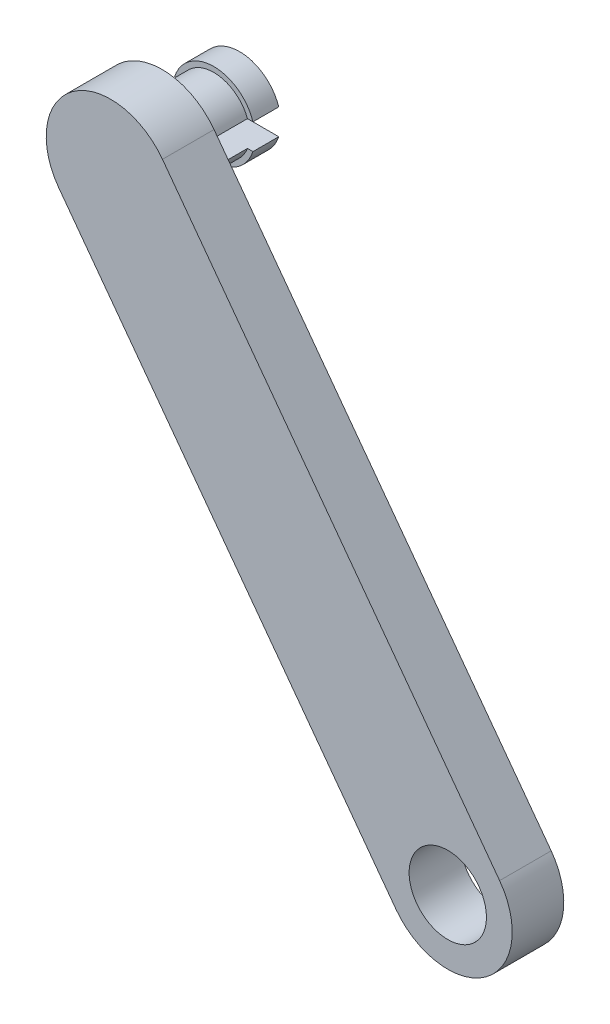
SolidWorks part; units mm, degrees
ref_plane "Plan de face" through (0, 0, 0) normal (0, 0, 1) x (1, 0, 0)
ref_plane "Plan de dessus" through (0, 0, 0) normal (0, 1, 0) x (1, 0, 0)
ref_plane "Plan de droite" through (0, 0, 0) normal (1, 0, 0) x (0, 0, -1)
sketch "Esquisse2" plane through (0, 0, 0) normal (0, 0, 1) x (1, 0, 0)
  line L0 (0, -5) -> (-13.0771, 12.6915) construction
  line L1 (-2.0104, -6.486) -> (-15.0875, 11.2054)
  line L2 (2.0104, -3.514) -> (-11.0667, 14.1775)
  arc A0 (-2.0104, -6.486) -> (2.0104, -3.514) centre (0, -5) ccw
  arc A1 (-11.0667, 14.1775) -> (-15.0875, 11.2054) centre (-13.0771, 12.6915) ccw
  point P4 (-6.5386, 3.8457)
  dimension "D1" = 5
extrude "Boss.-Extru.1" add sketch "Esquisse2" along normal blind 2
sketch "Esquisse3" plane through (0, 0, 2) normal (0, 0, 1) x (1, 0, 0)
  circle A0 centre (0, -5) radius 1.5
  dimension "D1" = 3
extrude "Enlèv. mat.-Extru.1" cut sketch "Esquisse3" against normal blind 2
sketch "Esquisse4" plane through (0, 0, 2) normal (0, 0, 1) x (1, 0, 0)
  circle A0 centre (-13.0771, 12.6915) radius 1.4
  dimension "D1" = 2.8
extrude "Boss.-Extru.2" add sketch "Esquisse4" against normal blind 2 from offset 2 offset against normal yes
sketch "Esquisse5" plane through (0, 0, -2) normal (0, 0, -1) x (-1, 0, 0)
  circle A0 centre (13.0771, 12.6915) radius 1.6
  dimension "D1" = 3.2
extrude "Boss.-Extru.3" add sketch "Esquisse5" along normal blind 1
sketch "Esquisse6" plane through (0, 0, -3) normal (0, 0, -1) x (-1, 0, 0)
  line L1 (11.0771, 13.1915) -> (15.0771, 13.1915)
  line L2 (11.0771, 13.1915) -> (11.0771, 12.1915)
  line L3 (11.0771, 12.1915) -> (15.0771, 12.1915)
  line L4 (15.0771, 13.1915) -> (15.0771, 12.1915)
  dimension "D1" = 0.5
  dimension "D2" = 0.5
  dimension "D3" = 4
  dimension "D4" = 2
extrude "Enlèv. mat.-Extru.2" cut sketch "Esquisse6" against normal blind 3
